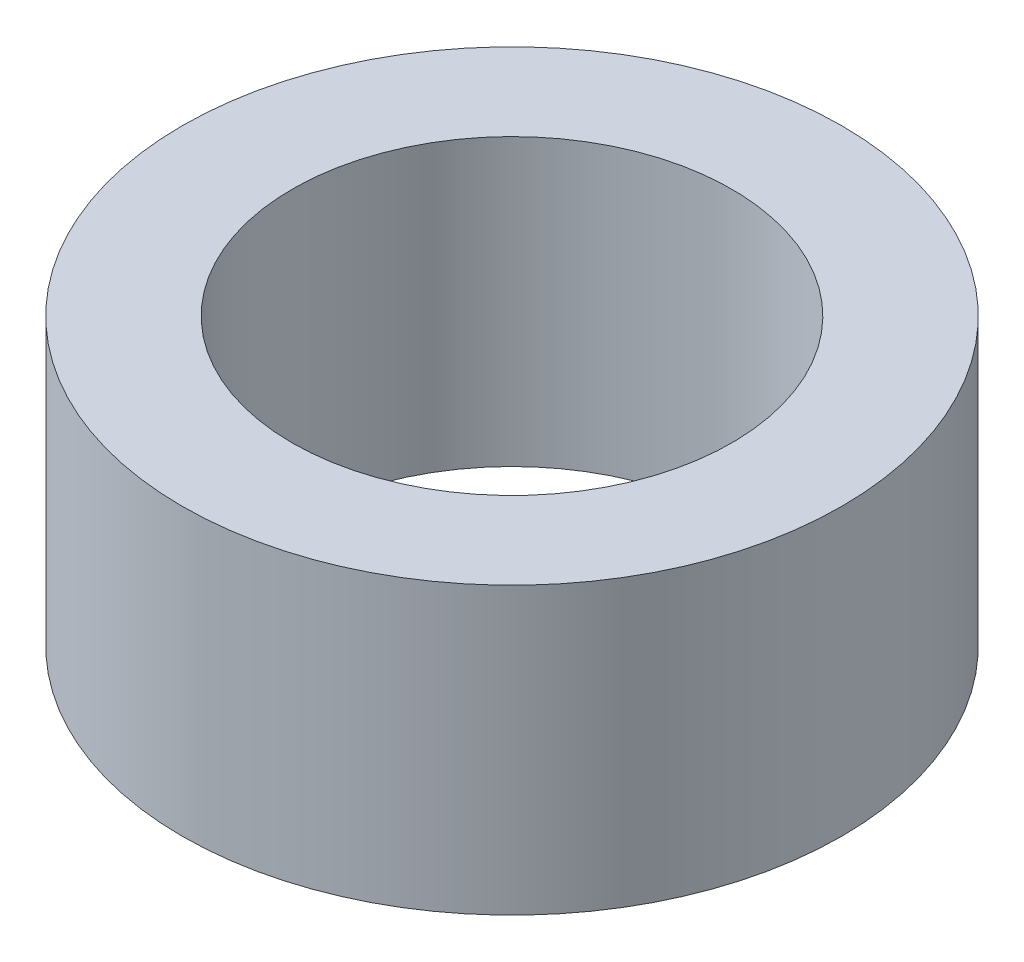
SolidWorks part; units mm, degrees
material "尼龙 101"
ref_plane "前视基准面" through (0, 0, 0) normal (0, 0, 1) x (1, 0, 0)
ref_plane "上视基准面" through (0, 0, 0) normal (0, 1, 0) x (1, 0, 0)
ref_plane "右视基准面" through (0, 0, 0) normal (1, 0, 0) x (0, 0, -1)
sketch "草图1" plane through (0, 0, 0) normal (0, 1, 0) x (1, 0, 0)
  circle A0 centre (0, 0) radius 2
  circle A1 centre (0, 0) radius 3
  dimension "D1" = 4
  dimension "D2" = 6
extrude "凸台-拉伸1" add sketch "草图1" along normal blind 2.6
